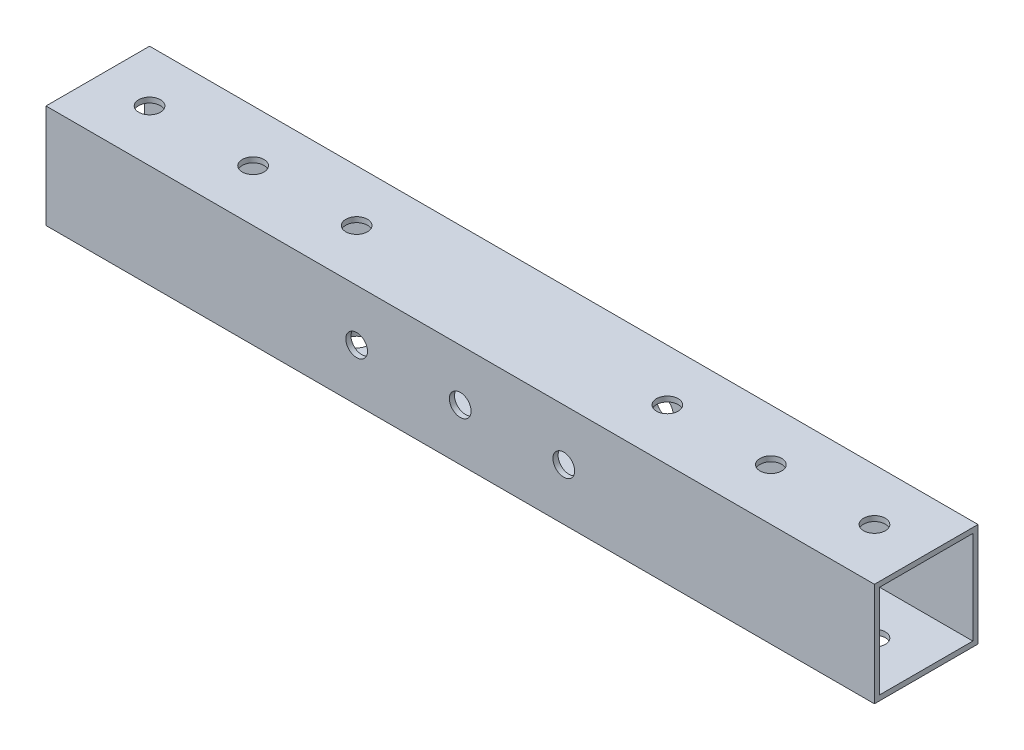
SolidWorks part; units mm, degrees
ref_plane "前视基准面" through (0, 0, 0) normal (0, 0, 1) x (1, 0, 0)
ref_plane "上视基准面" through (0, 0, 0) normal (0, 1, 0) x (1, 0, 0)
ref_plane "右视基准面" through (0, 0, 0) normal (1, 0, 0) x (0, 0, -1)
sketch "草图1" plane through (0, 0, 0) normal (1, 0, 0) x (0, 0, -1)
  line L1 (-10, 10) -> (10, 10)
  line L2 (-10, 10) -> (-10, -10)
  line L3 (-10, -10) -> (10, -10)
  line L4 (10, 10) -> (10, -10)
  line L5 (-10, 10) -> (10, -10) construction
  line L6 (-10, -10) -> (10, 10) construction
  point P0 (0, 0)
  dimension "D1" = 20
  dimension "D2" = 20
extrude "凸台-拉伸1" add sketch "草图1" along normal blind 160
sketch "草图2" plane through (0, -10, 0) normal (0, -1, 0) x (1, 0, 0)
  line L0 (0, 10) -> (0, -10) construction
  line L1 (160, 10) -> (0, 10) construction
  line L2 (80, 10) -> (80, -10) construction
  line L3 (160, -10) -> (0, -10) construction
  circle A0 centre (10, 0) radius 2.1
  circle A1 centre (30, 0) radius 2.1
  circle A2 centre (50, 0) radius 2.1
  circle A3 centre (110, 0) radius 2.1
  circle A4 centre (130, 0) radius 2.1
  circle A5 centre (150, 0) radius 2.1
  dimension "D1" = 10
  dimension "D3" = 4.2
  dimension "D2" = 10
  dimension "D5" = 20
  dimension "D4" = 3
extrude "切除-拉伸1" cut sketch "草图2" against normal blind 160
sketch "草图3" plane through (0, 0, 10) normal (0, 0, 1) x (1, 0, 0)
  line L0 (80, 10) -> (80, -10) construction
  line L1 (160, 10) -> (0, 10) construction
  line L2 (160, -10) -> (0, -10) construction
  circle A0 centre (60, 0) radius 2.1
  circle A1 centre (80, 0) radius 2.1
  circle A2 centre (100, 0) radius 2.1
  dimension "D1" = 10
  dimension "D2" = 4.2
  dimension "D5" = 20
  dimension "D3" = 20
  dimension "D4" = 3
extrude "切除-拉伸2" cut sketch "草图3" against normal through all
sketch "草图4" plane through (0, 0, 0) normal (-1, 0, 0) x (0, 0, 1)
  line L1 (-9, 9) -> (9, 9)
  line L2 (-9, 9) -> (-9, -9)
  line L3 (-9, -9) -> (9, -9)
  line L4 (9, 9) -> (9, -9)
  line L5 (-9, 9) -> (9, -9) construction
  line L6 (-9, -9) -> (9, 9) construction
  point P0 (0, 0)
  dimension "D1" = 18
  dimension "D2" = 18
extrude "切除-拉伸3" cut sketch "草图4" against normal through all
